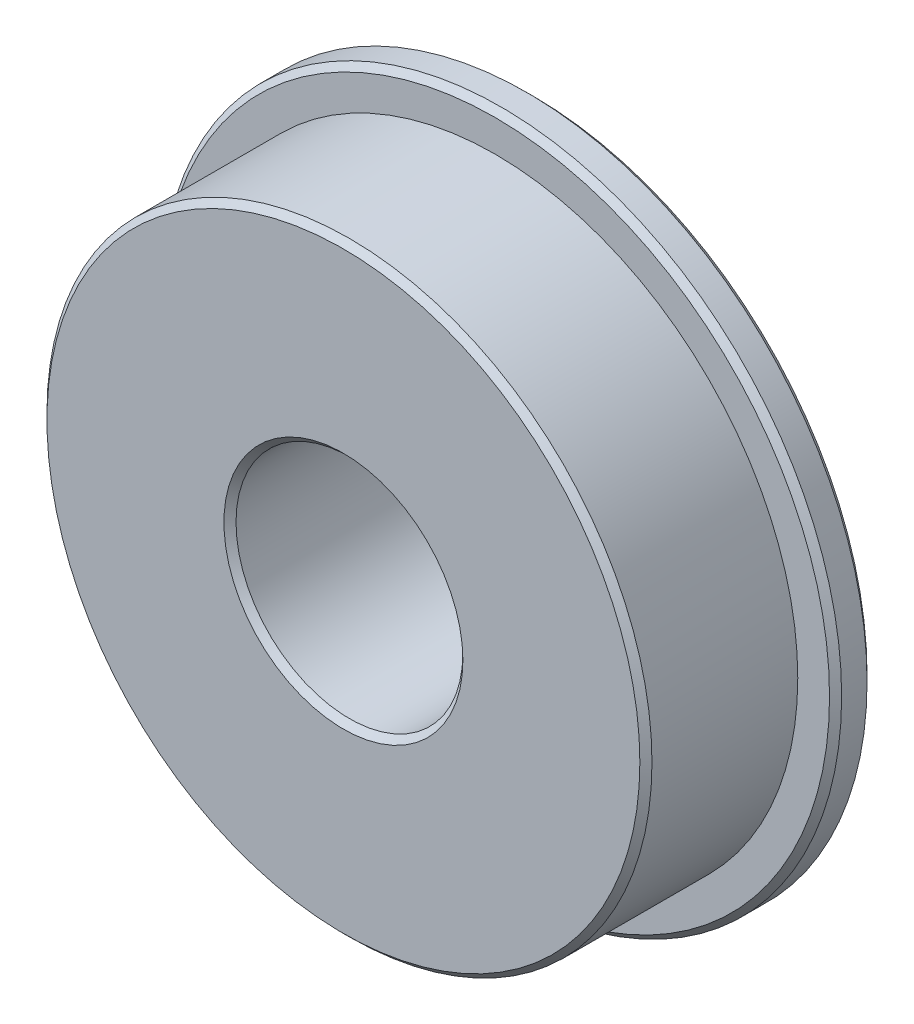
SolidWorks part; units mm, degrees
ref_plane "Front Plane" through (0, 0, 0) normal (0, 0, 1) x (1, 0, 0)
ref_plane "Top Plane" through (0, 0, 0) normal (0, 1, 0) x (1, 0, 0)
ref_plane "Right Plane" through (0, 0, 0) normal (1, 0, 0) x (0, 0, -1)
ref_plane "Plane1" through (0, 6.042, 0) normal (0, 1, 0) x (-1, 0, 0)
sketch "Sketch1" plane through (0, 6.042, 0) normal (0, 1, 0) x (-1, 0, 0)
  line L0 (-5.172, 7.9502) -> (-5.426, 7.6962)
  line L1 (-5.426, 7.6962) -> (-5.426, 1.5748)
  line L2 (-5.426, 1.5748) -> (-6.7595, 1.5748)
  line L3 (-6.7595, 1.5748) -> (-7.0135, 1.3208)
  line L4 (-7.0135, 1.3208) -> (-7.0135, 0.254)
  line L5 (-7.0135, 0.254) -> (-6.7595, 0)
  line L6 (-6.7595, 0) -> (2.2575, 0)
  line L7 (2.2575, 0) -> (2.5115, 0.254)
  line L8 (2.5115, 0.254) -> (2.5115, 7.6962)
  line L9 (2.5115, 7.6962) -> (2.2575, 7.9502)
  line L10 (2.2575, 7.9502) -> (-5.172, 7.9502)
  line L11 (7.274, 0) -> (7.274, 7.9502) construction
  dimension "D1" = 4.7625
revolve "Revolve1" add sketch "Sketch1" angle 360 about L11
